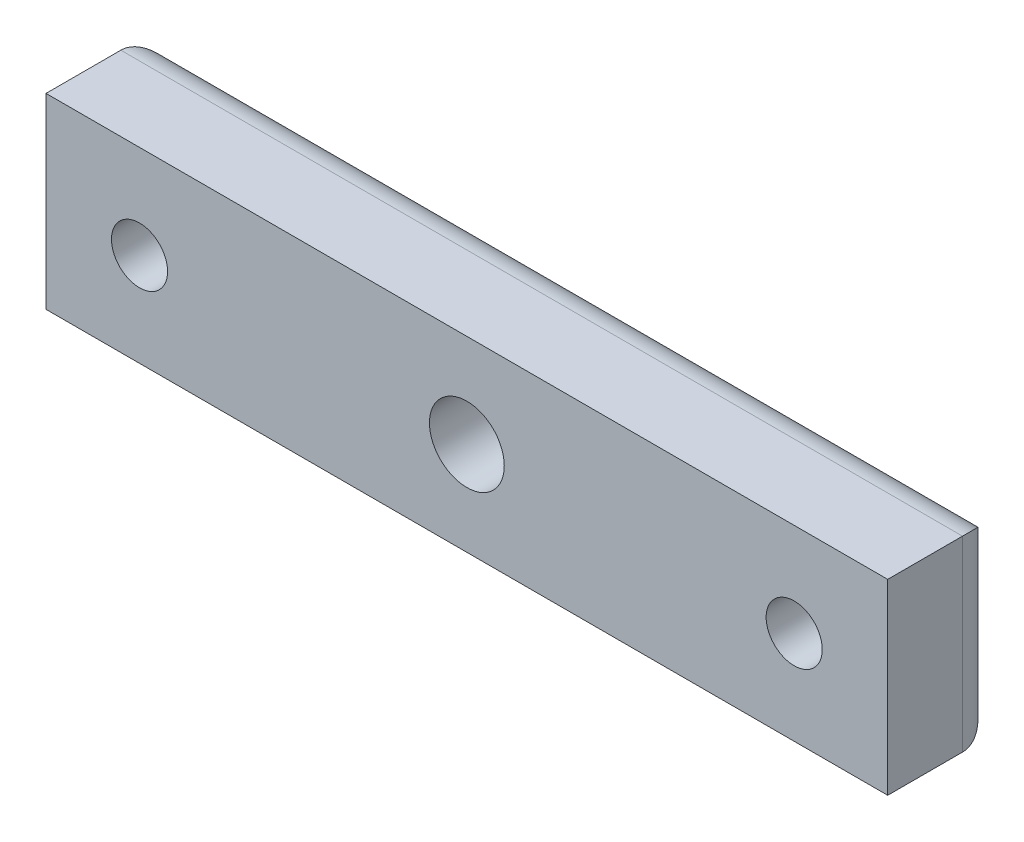
SolidWorks part; units mm, degrees
ref_plane "Plan de face" through (0, 0, 0) normal (0, 0, 1) x (1, 0, 0)
ref_plane "Plan de dessus" through (0, 0, 0) normal (0, 1, 0) x (1, 0, 0)
ref_plane "Plan de droite" through (0, 0, 0) normal (1, 0, 0) x (0, 0, -1)
sketch "Esquisse1" plane through (0, 0, 0) normal (0, 0, 1) x (1, 0, 0)
  line L0 (0, 5) -> (45, 5) construction
  line L1 (0, 0) -> (45, 0)
  line L2 (0, 0) -> (0, 10)
  line L3 (0, 10) -> (45, 10)
  line L4 (45, 0) -> (45, 10)
  circle A0 centre (5, 5) radius 1.5
  circle A1 centre (22.5, 5) radius 2
  circle A2 centre (40, 5) radius 1.5
  point P13 (5.5666, 7.5)
  point P14 (21.8888, 7.5)
  point P15 (38.3548, 7.5)
  point P16 (18.725, 7.5)
  point P17 (22.5, 5)
  dimension "D3" = 3
  dimension "D4" = 4
  dimension "D5" = 3
  dimension "D1" = 45
  dimension "D2" = 10
  dimension "D6" = 5
  dimension "D7" = 5
extrude "Boss.-Extru.1" add sketch "Esquisse1" along normal blind 6
fillet "Congé1" radius 2 4 edges at (22.5, 10, 0) (45, 5, 0) (22.5, 0, 0) (0, 5, 0)
